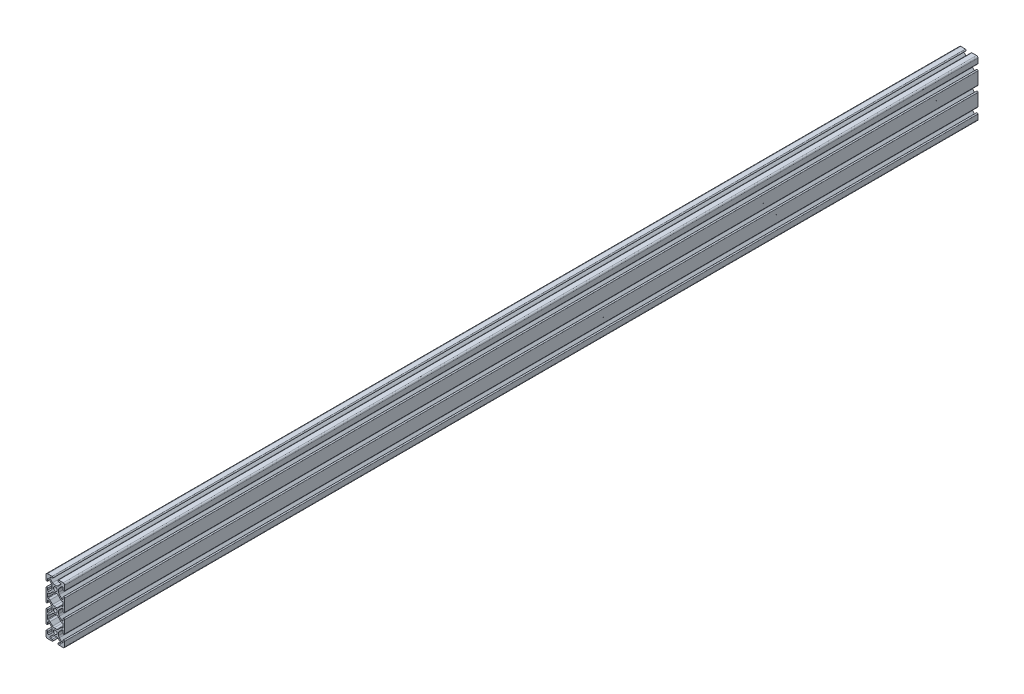
SolidWorks part; units mm, degrees
material "6105-T5"
ref_plane "Front Plane" through (0, 0, 0) normal (0, 0, 1) x (1, 0, 0)
ref_plane "Top Plane" through (0, 0, 0) normal (0, 1, 0) x (1, 0, 0)
ref_plane "Right Plane" through (0, 0, 0) normal (1, 0, 0) x (0, 0, -1)
sketch "Sketch1" plane through (0, 0, 0) normal (0, 0, 1) x (1, 0, 0)
  line L0 (9.3698, 15.43) -> (9.6, 15.43)
  line L1 (10.36, 14.67) -> (10.36, 10.3305)
  line L2 (9.6, 9.5705) -> (9.3698, 9.5705)
  line L3 (7.1282, 8.6419) -> (3.79, 5.3032)
  line L4 (1.5485, 4.3748) -> (-1.5485, 4.3748)
  line L5 (-3.79, 5.3032) -> (-7.1283, 8.6415)
  line L6 (-9.3698, 9.57) -> (-9.6, 9.57)
  line L7 (-10.36, 10.33) -> (-10.36, 14.6695)
  line L8 (-9.6, 15.4295) -> (-9.3698, 15.4295)
  line L9 (-7.1282, 16.3581) -> (-3.79, 19.6968)
  line L10 (-1.5485, 20.6252) -> (1.5485, 20.6252)
  line L11 (3.79, 19.6968) -> (7.1283, 16.3585)
  line L12 (9.3698, 40.43) -> (9.6, 40.43)
  line L13 (10.36, 39.67) -> (10.36, 35.3305)
  line L14 (9.6, 34.5705) -> (9.3698, 34.5705)
  line L15 (7.1282, 33.6419) -> (3.79, 30.3032)
  line L16 (1.5485, 29.3748) -> (-1.5485, 29.3748)
  line L17 (-3.79, 30.3032) -> (-7.1283, 33.6415)
  line L18 (-9.3698, 34.57) -> (-9.6, 34.57)
  line L19 (-10.36, 35.33) -> (-10.36, 39.6695)
  line L20 (-9.6, 40.4295) -> (-9.3698, 40.4295)
  line L21 (-7.1282, 41.3581) -> (-3.79, 44.6968)
  line L22 (-1.5485, 45.6252) -> (1.5485, 45.6252)
  line L23 (3.79, 44.6968) -> (7.1283, 41.3585)
  line L24 (10.36, 56.43) -> (10.36, 54.32)
  line L25 (12.5, 54.32) -> (12.5, 60.5)
  line L26 (10.5, 62.5) -> (4.32, 62.5)
  line L27 (4.32, 60.36) -> (6.4295, 60.36)
  line L28 (7.1394, 58.6531) -> (3.79, 55.3032)
  line L29 (1.5485, 54.3748) -> (-1.5485, 54.3748)
  line L30 (-3.79, 55.3032) -> (-7.1384, 58.6516)
  line L31 (-6.43, 60.36) -> (-4.32, 60.36)
  line L32 (-4.32, 62.5) -> (-10.5, 62.5)
  line L33 (-12.5, 60.5) -> (-12.5, 54.32)
  line L34 (-10.36, 54.32) -> (-10.36, 56.4295)
  line L35 (-8.6531, 57.1394) -> (-5.3032, 53.79)
  line L36 (-4.3748, 51.5485) -> (-4.3748, 48.4515)
  line L37 (-5.3032, 46.21) -> (-8.6516, 42.8616)
  line L38 (-10.36, 43.57) -> (-10.36, 45.68)
  line L39 (-12.5, 45.68) -> (-12.5, 29.32)
  line L40 (-10.36, 29.32) -> (-10.36, 31.4295)
  line L41 (-8.6531, 32.1394) -> (-5.3032, 28.79)
  line L42 (-4.3748, 26.5485) -> (-4.3748, 23.4515)
  line L43 (-5.3032, 21.21) -> (-8.6516, 17.8616)
  line L44 (-10.36, 18.57) -> (-10.36, 20.68)
  line L45 (-12.5, 20.68) -> (-12.5, 4.32)
  line L46 (-10.36, 4.32) -> (-10.36, 6.4295)
  line L47 (-8.6531, 7.1394) -> (-5.3032, 3.79)
  line L48 (-4.3748, 1.5485) -> (-4.3748, -1.5485)
  line L49 (-5.3032, -3.79) -> (-8.6516, -7.1384)
  line L50 (-10.36, -6.43) -> (-10.36, -4.32)
  line L51 (-12.5, -4.32) -> (-12.5, -10.5)
  line L52 (-10.5, -12.5) -> (-4.32, -12.5)
  line L53 (-4.32, -10.36) -> (-6.4295, -10.36)
  line L54 (-7.1394, -8.6531) -> (-3.79, -5.3032)
  line L55 (-1.5485, -4.3748) -> (1.5485, -4.3748)
  line L56 (3.79, -5.3032) -> (7.1384, -8.6516)
  line L57 (6.43, -10.36) -> (4.32, -10.36)
  line L58 (4.32, -12.5) -> (10.5, -12.5)
  line L59 (12.5, -10.5) -> (12.5, -4.32)
  line L60 (10.36, -4.32) -> (10.36, -6.4295)
  line L61 (8.6531, -7.1394) -> (5.3032, -3.79)
  line L62 (4.3748, -1.5485) -> (4.3748, 1.5485)
  line L63 (5.3032, 3.79) -> (8.6516, 7.1384)
  line L64 (10.36, 6.4301) -> (10.36, 4.32)
  line L65 (12.5, 4.32) -> (12.5, 20.68)
  line L66 (10.36, 20.68) -> (10.36, 18.5705)
  line L67 (8.6531, 17.8606) -> (5.3032, 21.21)
  line L68 (4.3748, 23.4515) -> (4.3748, 26.5485)
  line L69 (5.3032, 28.79) -> (8.6516, 32.1384)
  line L70 (10.36, 31.43) -> (10.36, 29.32)
  line L71 (12.5, 29.32) -> (12.5, 45.68)
  line L72 (10.36, 45.68) -> (10.36, 43.5705)
  line L73 (8.6531, 42.8606) -> (5.3032, 46.21)
  line L74 (4.3748, 48.4515) -> (4.3748, 51.5485)
  line L75 (5.3032, 53.79) -> (8.6516, 57.1384)
  circle A0 centre (0, 0) radius 2.5
  arc A1 (7.1283, 16.3585) -> (9.3698, 15.43) centre (9.3698, 18.6) ccw
  arc A2 (10.36, 14.67) -> (9.6, 15.43) centre (9.6, 14.67) ccw
  arc A3 (9.6, 9.5705) -> (10.36, 10.3305) centre (9.6, 10.3305) ccw
  arc A4 (9.3698, 9.5705) -> (7.1282, 8.6419) centre (9.3698, 6.4005) ccw
  arc A5 (1.5485, 4.3748) -> (3.79, 5.3032) centre (1.5485, 7.5448) ccw
  arc A6 (-3.79, 5.3032) -> (-1.5485, 4.3748) centre (-1.5485, 7.5448) ccw
  arc A7 (-7.1283, 8.6415) -> (-9.3698, 9.57) centre (-9.3698, 6.4) ccw
  arc A8 (-10.36, 10.33) -> (-9.6, 9.57) centre (-9.6, 10.33) ccw
  arc A9 (-9.6, 15.4295) -> (-10.36, 14.6695) centre (-9.6, 14.6695) ccw
  arc A10 (-9.3698, 15.4295) -> (-7.1282, 16.3581) centre (-9.3698, 18.5995) ccw
  arc A11 (-1.5485, 20.6252) -> (-3.79, 19.6968) centre (-1.5485, 17.4552) ccw
  arc A12 (3.79, 19.6968) -> (1.5485, 20.6252) centre (1.5485, 17.4552) ccw
  circle A13 centre (0, 25) radius 2.5
  circle A14 centre (0, 50) radius 2.5
  arc A15 (7.1283, 41.3585) -> (9.3698, 40.43) centre (9.3698, 43.6) ccw
  arc A16 (10.36, 39.67) -> (9.6, 40.43) centre (9.6, 39.67) ccw
  arc A17 (9.6, 34.5705) -> (10.36, 35.3305) centre (9.6, 35.3305) ccw
  arc A18 (9.3698, 34.5705) -> (7.1282, 33.6419) centre (9.3698, 31.4005) ccw
  arc A19 (1.5485, 29.3748) -> (3.79, 30.3032) centre (1.5485, 32.5448) ccw
  arc A20 (-3.79, 30.3032) -> (-1.5485, 29.3748) centre (-1.5485, 32.5448) ccw
  arc A21 (-7.1283, 33.6415) -> (-9.3698, 34.57) centre (-9.3698, 31.4) ccw
  arc A22 (-10.36, 35.33) -> (-9.6, 34.57) centre (-9.6, 35.33) ccw
  arc A23 (-9.6, 40.4295) -> (-10.36, 39.6695) centre (-9.6, 39.6695) ccw
  arc A24 (-9.3698, 40.4295) -> (-7.1282, 41.3581) centre (-9.3698, 43.5995) ccw
  arc A25 (-1.5485, 45.6252) -> (-3.79, 44.6968) centre (-1.5485, 42.4552) ccw
  arc A26 (3.79, 44.6968) -> (1.5485, 45.6252) centre (1.5485, 42.4552) ccw
  arc A27 (10.36, 54.32) -> (12.5, 54.32) centre (11.43, 54.32) ccw
  arc A28 (12.5, 60.5) -> (10.5, 62.5) centre (10.5, 60.5) ccw
  arc A29 (4.32, 62.5) -> (4.32, 60.36) centre (4.32, 61.43) ccw
  arc A30 (7.1394, 58.6531) -> (6.4295, 60.36) centre (6.4285, 59.3585) ccw
  arc A31 (1.5485, 54.3748) -> (3.79, 55.3032) centre (1.5485, 57.5448) ccw
  arc A32 (-3.79, 55.3032) -> (-1.5485, 54.3748) centre (-1.5485, 57.5448) ccw
  arc A33 (-6.43, 60.36) -> (-7.1384, 58.6516) centre (-6.429, 59.3585) ccw
  arc A34 (-4.32, 60.36) -> (-4.32, 62.5) centre (-4.32, 61.43) ccw
  arc A35 (-10.5, 62.5) -> (-12.5, 60.5) centre (-10.5, 60.5) ccw
  arc A36 (-12.5, 54.32) -> (-10.36, 54.32) centre (-11.43, 54.32) ccw
  arc A37 (-8.6531, 57.1394) -> (-10.36, 56.4295) centre (-9.3585, 56.4285) ccw
  arc A38 (-4.3748, 51.5485) -> (-5.3032, 53.79) centre (-7.5448, 51.5485) ccw
  arc A39 (-5.3032, 46.21) -> (-4.3748, 48.4515) centre (-7.5448, 48.4515) ccw
  arc A40 (-10.36, 43.57) -> (-8.6516, 42.8616) centre (-9.3585, 43.571) ccw
  arc A41 (-10.36, 45.68) -> (-12.5, 45.68) centre (-11.43, 45.68) ccw
  arc A42 (-12.5, 29.32) -> (-10.36, 29.32) centre (-11.43, 29.32) ccw
  arc A43 (-8.6531, 32.1394) -> (-10.36, 31.4295) centre (-9.3585, 31.4285) ccw
  arc A44 (-4.3748, 26.5485) -> (-5.3032, 28.79) centre (-7.5448, 26.5485) ccw
  arc A45 (-5.3032, 21.21) -> (-4.3748, 23.4515) centre (-7.5448, 23.4515) ccw
  arc A46 (-10.36, 18.57) -> (-8.6516, 17.8616) centre (-9.3585, 18.571) ccw
  arc A47 (-10.36, 20.68) -> (-12.5, 20.68) centre (-11.43, 20.68) ccw
  arc A48 (-12.5, 4.32) -> (-10.36, 4.32) centre (-11.43, 4.32) ccw
  arc A49 (-8.6531, 7.1394) -> (-10.36, 6.4295) centre (-9.3585, 6.4285) ccw
  arc A50 (-4.3748, 1.5485) -> (-5.3032, 3.79) centre (-7.5448, 1.5485) ccw
  arc A51 (-5.3032, -3.79) -> (-4.3748, -1.5485) centre (-7.5448, -1.5485) ccw
  arc A52 (-10.36, -6.43) -> (-8.6516, -7.1384) centre (-9.3585, -6.429) ccw
  arc A53 (-10.36, -4.32) -> (-12.5, -4.32) centre (-11.43, -4.32) ccw
  arc A54 (-12.5, -10.5) -> (-10.5, -12.5) centre (-10.5, -10.5) ccw
  arc A55 (-4.32, -12.5) -> (-4.32, -10.36) centre (-4.32, -11.43) ccw
  arc A56 (-7.1394, -8.6531) -> (-6.4295, -10.36) centre (-6.4285, -9.3585) ccw
  arc A57 (-1.5485, -4.3748) -> (-3.79, -5.3032) centre (-1.5485, -7.5448) ccw
  arc A58 (3.79, -5.3032) -> (1.5485, -4.3748) centre (1.5485, -7.5448) ccw
  arc A59 (6.43, -10.36) -> (7.1384, -8.6516) centre (6.429, -9.3585) ccw
  arc A60 (4.32, -10.36) -> (4.32, -12.5) centre (4.32, -11.43) ccw
  arc A61 (10.5, -12.5) -> (12.5, -10.5) centre (10.5, -10.5) ccw
  arc A62 (12.5, -4.32) -> (10.36, -4.32) centre (11.43, -4.32) ccw
  arc A63 (8.6531, -7.1394) -> (10.36, -6.4295) centre (9.3585, -6.4285) ccw
  arc A64 (4.3748, -1.5485) -> (5.3032, -3.79) centre (7.5448, -1.5485) ccw
  arc A65 (5.3032, 3.79) -> (4.3748, 1.5485) centre (7.5448, 1.5485) ccw
  arc A66 (10.36, 6.4301) -> (8.6516, 7.1384) centre (9.3585, 6.429) ccw
  arc A67 (10.36, 4.32) -> (12.5, 4.32) centre (11.43, 4.32) ccw
  arc A68 (12.5, 20.68) -> (10.36, 20.68) centre (11.43, 20.68) ccw
  arc A69 (8.6531, 17.8606) -> (10.36, 18.5705) centre (9.3585, 18.5715) ccw
  arc A70 (4.3748, 23.4515) -> (5.3032, 21.21) centre (7.5448, 23.4515) ccw
  arc A71 (5.3032, 28.79) -> (4.3748, 26.5485) centre (7.5448, 26.5485) ccw
  arc A72 (10.36, 31.43) -> (8.6516, 32.1384) centre (9.3585, 31.429) ccw
  arc A73 (10.36, 29.32) -> (12.5, 29.32) centre (11.43, 29.32) ccw
  arc A74 (12.5, 45.68) -> (10.36, 45.68) centre (11.43, 45.68) ccw
  arc A75 (8.6531, 42.8606) -> (10.36, 43.5705) centre (9.3585, 43.5715) ccw
  arc A76 (4.3748, 48.4515) -> (5.3032, 46.21) centre (7.5448, 48.4515) ccw
  arc A77 (5.3032, 53.79) -> (4.3748, 51.5485) centre (7.5448, 51.5485) ccw
  arc A78 (10.36, 56.43) -> (8.6516, 57.1384) centre (9.3585, 56.429) ccw
  point P0 (-12.5, 62.5)
  point P1 (0, 62.5)
  point P2 (12.5, 62.5)
  point P237 (12.5, 50)
  point P238 (-12.5, 50)
  point P239 (0, 50)
  point P240 (12.5, 37.5)
  point P241 (0, 37.5)
  point P242 (-12.5, 37.5)
  point P243 (-12.5, 25)
  point P244 (0, 25)
  point P245 (12.5, 25)
  point P246 (12.5, 12.5)
  point P247 (0, 12.5)
  point P248 (-12.5, 12.5)
  point P249 (-12.5, 0)
  point P250 (12.5, 0)
  point P251 (-12.5, -12.5)
  point P252 (0, -12.5)
  point P253 (12.5, -12.5)
extrude "Extrude1" add sketch "Sketch1" against normal blind 1219.2
